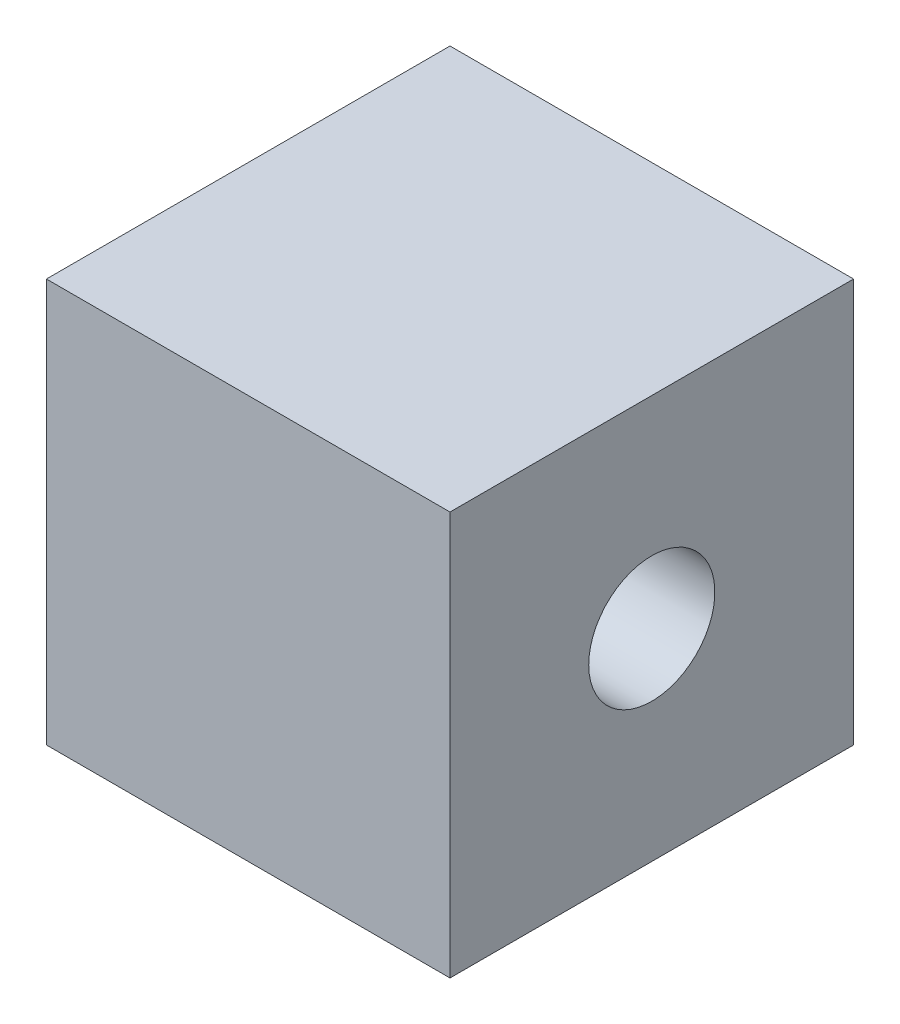
SolidWorks part; units mm, degrees
ref_plane "前视基准面" through (0, 0, 0) normal (0, 0, 1) x (1, 0, 0)
ref_plane "上视基准面" through (0, 0, 0) normal (0, 1, 0) x (1, 0, 0)
ref_plane "右视基准面" through (0, 0, 0) normal (1, 0, 0) x (0, 0, -1)
sketch "草图1" plane through (0, 0, 0) normal (0, 1, 0) x (1, 0, 0)
  line L1 (0, 0) -> (8, 0)
  line L2 (0, 0) -> (0, 8)
  line L3 (0, 8) -> (8, 8)
  line L4 (8, 0) -> (8, 8)
  dimension "D1" = 8
  dimension "D2" = 8
extrude "凸台-拉伸1" add sketch "草图1" along normal blind 8
sketch "草图2" plane through (0, 0, 0) normal (-1, 0, 0) x (0, 0, 1)
  line L0 (-8, 8) -> (-8, 0) construction
  line L1 (-8, 8) -> (0, 8) construction
  circle A0 centre (-4, 4) radius 1.25
  dimension "D1" = 2.5
  dimension "D2" = 4
  dimension "D3" = 4
extrude "切除-拉伸1" cut sketch "草图2" against normal blind 8
cosmetic thread "装饰螺纹线1" parameters "D2"=3
